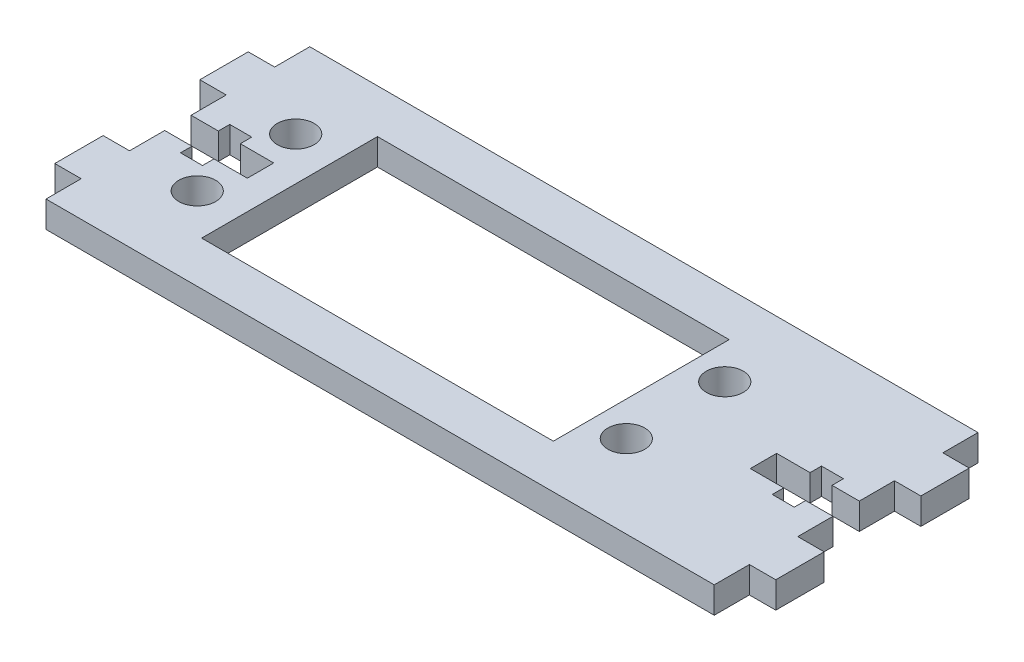
SolidWorks part; units mm, degrees
ref_plane "Front Plane" through (0, 0, 0) normal (0, 0, 1) x (1, 0, 0)
ref_plane "Top Plane" through (0, 0, 0) normal (0, 1, 0) x (1, 0, 0)
ref_plane "Right Plane" through (0, 0, 0) normal (1, 0, 0) x (0, 0, -1)
sketch "Sketch1" plane through (0, 0, 0) normal (0, 1, 0) x (1, 0, 0)
  line L0 (-38, 30) -> (-38, 0) construction
  line L1 (0, 0) -> (-76, 0)
  line L2 (0, 0) -> (0, 4)
  line L3 (0, 30) -> (-76, 30)
  line L4 (-76, 0) -> (-76, 4)
  line L5 (-66.6, 15) -> (-63.3, 15) construction
  line L6 (-23.3, 25) -> (-23.3, 5)
  line L8 (-23.3, 25) -> (-63.3, 25)
  line L9 (-63.3, 25) -> (-63.3, 5)
  line L10 (-63.3, 5) -> (-23.3, 5)
  line L11 (0, 16.5) -> (-3.1, 16.5)
  line L12 (-3.1, 16.5) -> (-3.1, 17.8)
  line L13 (-3.1, 17.8) -> (-5.6, 17.8)
  line L14 (-5.6, 17.8) -> (-5.6, 16.5)
  line L15 (-5.6, 16.5) -> (-9.4, 16.5)
  line L16 (-9.4, 16.5) -> (-9.4, 13.5)
  line L17 (-9.4, 13.5) -> (-5.6, 13.5)
  line L18 (-5.6, 13.5) -> (-5.6, 12.2)
  line L19 (-5.6, 12.2) -> (-3.1, 12.2)
  line L20 (-3.1, 12.2) -> (-3.1, 13.5)
  line L21 (-3.1, 13.5) -> (0, 13.5)
  line L22 (0, 16.5) -> (0, 20.5)
  line L23 (-72.9, 17.8) -> (-70.4, 17.8)
  line L24 (-70.4, 17.8) -> (-70.4, 16.5)
  line L25 (-70.4, 16.5) -> (-66.6, 16.5)
  line L26 (-66.6, 16.5) -> (-66.6, 13.5)
  line L27 (-66.6, 13.5) -> (-70.4, 13.5)
  line L28 (-70.4, 13.5) -> (-70.4, 12.2)
  line L29 (-70.4, 12.2) -> (-72.9, 12.2)
  line L30 (-72.9, 12.2) -> (-72.9, 13.5)
  line L31 (-72.9, 16.5) -> (-72.9, 17.8)
  line L32 (-72.9, 13.5) -> (-76, 13.5)
  line L33 (-76, 16.5) -> (-72.9, 16.5)
  line L34 (-76, 16.5) -> (-76, 20.5)
  line L35 (0, 26) -> (3, 26)
  line L36 (3, 26) -> (3, 20.5)
  line L37 (3, 20.5) -> (0, 20.5)
  line L38 (0, 26) -> (0, 30)
  line L39 (0, 4) -> (3, 4)
  line L40 (3, 4) -> (3, 9.5)
  line L41 (3, 9.5) -> (0, 9.5)
  line L42 (0, 9.5) -> (0, 13.5)
  line L43 (-76, 4) -> (-79, 4)
  line L44 (-79, 4) -> (-79, 9.5)
  line L45 (-79, 9.5) -> (-76, 9.5)
  line L46 (-79, 20.5) -> (-76, 20.5)
  line L47 (-76, 26) -> (-79, 26)
  line L48 (-79, 26) -> (-79, 20.5)
  line L49 (-76, 26) -> (-76, 30)
  line L50 (-76, 9.5) -> (-76, 13.5)
  line L55 (-19.3, 15) -> (-9.4, 15) construction
  circle A0 centre (-19.4, 20.6) radius 2.1
  circle A1 centre (-68.2, 20.6) radius 2.1
  circle A2 centre (-68.2, 9.4) radius 2.1
  circle A3 centre (-19.4, 9.4) radius 2.1
  point P8 (0, 26)
  dimension "D10" = 4.4
  dimension "D7" = 4.2
  dimension "D1" = 76
  dimension "D2" = 30
  dimension "D3" = 20
  dimension "D4" = 40
  dimension "D5" = 23.3
  dimension "D6" = 5
  dimension "D8" = 48.8
  dimension "D9" = 3.9
  dimension "D11" = 3
  dimension "D12" = 3.1
  dimension "D13" = 13.5
  dimension "D14" = 1.3
  dimension "D15" = 2.5
  dimension "D16" = 3.8
  dimension "D17" = 4
  dimension "D18" = 5.5
  dimension "D19" = 3
extrude "Boss-Extrude1" add sketch "Sketch1" along normal blind 3
